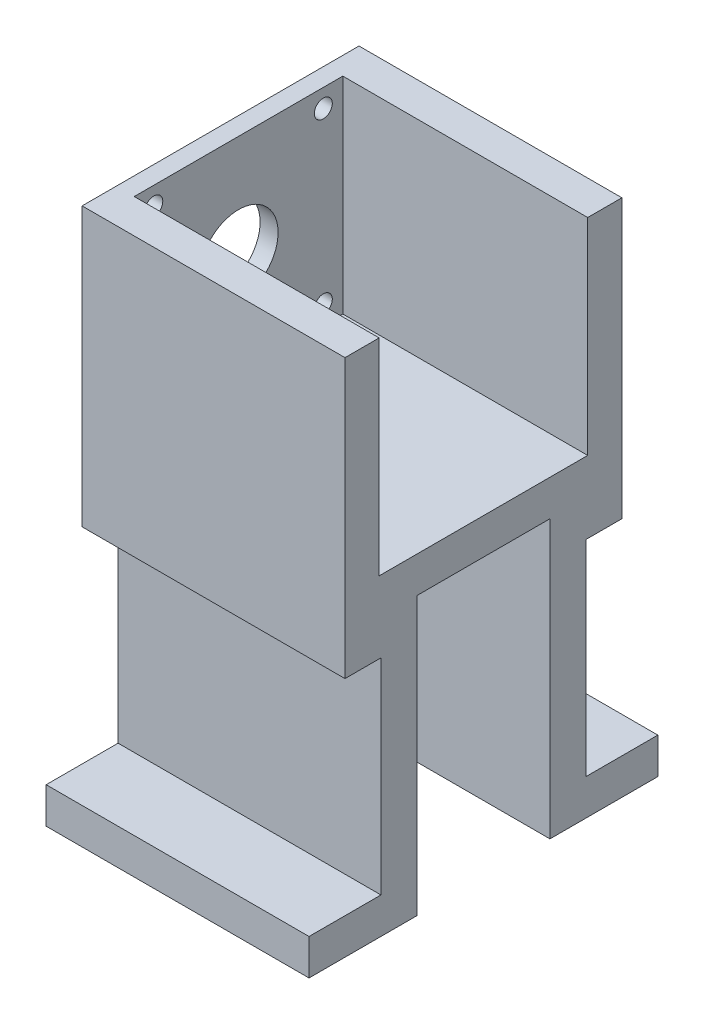
SolidWorks part; units mm, degrees
ref_plane "Front Plane" through (0, 0, 0) normal (0, 0, 1) x (1, 0, 0)
ref_plane "Top Plane" through (0, 0, 0) normal (0, 1, 0) x (1, 0, 0)
ref_plane "Right Plane" through (0, 0, 0) normal (1, 0, 0) x (0, 0, -1)
sketch "Sketch1" plane through (0, 0, 0) normal (0, 0, 1) x (1, 0, 0)
  line L0 (-34.05, 0) -> (34.05, 0)
  line L1 (-34.05, -10) -> (29.05, -10)
  line L2 (34.05, -10) -> (34.05, 0)
  line L3 (29.05, -10) -> (34.05, -10)
  line L4 (-39.05, 57.3) -> (-39.05, -10)
  line L7 (-34.05, -10) -> (-39.05, -10)
  line L8 (-39.05, 57.3) -> (-34.05, 57.3)
  line L9 (-34.05, 57.3) -> (-34.05, 0)
  dimension "D2" = 5
  dimension "D4" = 57.3
  dimension "D6" = 10
  dimension "D11" = 68.1
extrude "Boss-Extrude1" add sketch "Sketch1" along normal blind 57
sketch "Sketch4" plane through (-39.05, 0, 0) normal (-1, 0, 0) x (0, 0, 1)
  line L0 (28.5, 57.3) -> (28.5, 28.65) construction
  line L1 (57, 57.3) -> (0, 57.3) construction
  line L2 (4.93, 52.22) -> (28.5, 52.22) construction
  line L3 (52.07, 52.22) -> (28.5, 52.22) construction
  line L4 (28.5, 28.65) -> (57, 28.65) construction
  line L5 (57, 57.3) -> (57, -10) construction
  line L6 (52.07, 52.22) -> (52.07, 28.65) construction
  line L7 (52.07, 5.08) -> (52.07, 28.65) construction
  circle A0 centre (28.5, 28.65) radius 11
  circle A1 centre (52.07, 52.22) radius 2.5
  circle A2 centre (4.93, 52.22) radius 2.5
  circle A3 centre (52.07, 5.08) radius 2.5
  circle A4 centre (4.93, 5.08) radius 2.5
  dimension "D2" = 22
  dimension "D5" = 5
  dimension "D1" = 28.65
  dimension "D3" = 23.57
  dimension "D4" = 23.57
  dimension "D6" = 23.57
  dimension "D7" = 23.57
  dimension "D8" = 47.14
  dimension "D9" = 47.14
extrude "Cut-Extrude3" cut sketch "Sketch4" against normal blind 43
sketch "Sketch5" plane through (0, -10, 0) normal (0, -1, 0) x (1, 0, 0)
  line L0 (34.05, 57) -> (34.05, 0) construction
  line L1 (-39.05, 0) -> (34.05, 0)
  line L2 (-39.05, 0) -> (-39.05, 10)
  line L3 (-39.05, 10) -> (34.05, 10)
  line L4 (34.05, 0) -> (34.05, 10)
  line L5 (-39.05, 57) -> (-39.05, 0) construction
  line L6 (34.05, 57) -> (-39.05, 57)
  line L7 (34.05, 57) -> (34.05, 47)
  line L8 (34.05, 47) -> (-39.05, 47)
  line L9 (-39.05, 57) -> (-39.05, 47)
  dimension "D1" = 10
extrude "Boss-Extrude2" add sketch "Sketch5" along normal blind 77.1
sketch "Sketch6" plane through (0, 0, 0) normal (0, 0, -1) x (-1, 0, 0)
  line L0 (39.05, 57.3) -> (39.05, -87.1) construction
  line L1 (-34.05, -87.1) -> (39.05, -87.1)
  line L2 (-34.05, -87.1) -> (-34.05, -77.1)
  line L3 (-34.05, -77.1) -> (39.05, -77.1)
  line L4 (39.05, -87.1) -> (39.05, -77.1)
  dimension "D1" = 10
extrude "Boss-Extrude3" add sketch "Sketch6" along normal blind 20
ref_plane "Plane1" through (0, 0, 28.5) normal (0, 0, 1) x (1, 0, 0)
sketch "Sketch8" plane through (0, 0, 0) normal (0, 0, -1) x (-1, 0, 0)
  line L0 (-34.05, -77.1) -> (-34.05, 0) construction
  line L1 (39.05, 57.3) -> (-34.05, 57.3)
  line L2 (39.05, 57.3) -> (39.05, -20)
  line L3 (39.05, -20) -> (-34.05, -20)
  line L4 (-34.05, 57.3) -> (-34.05, -20)
  line L5 (-34.05, 0) -> (34.05, 0) construction
  dimension "D1" = 20
extrude "Boss-Extrude4" add sketch "Sketch8" along normal blind 10
mirror "Mirror2" about plane through (0, 0, 28.5) normal (0, 0, 1) of "Boss-Extrude4"
mirror "Mirror3" about plane through (0, 0, 28.5) normal (0, 0, 1) of "Boss-Extrude3"
sketch "Sketch9" plane through (0, 0, 57) normal (0, 0, -1) x (-1, 0, 0)
  line L4 (-34.05, 57.3) -> (-34.05, 0)
  line L5 (-34.05, 0) -> (34.05, 0)
  line L6 (34.05, 0) -> (34.05, 57.3)
  line L7 (34.05, 57.3) -> (-34.05, 57.3)
  line L8 (-34.05, 57.3) -> (-34.05, 0)
  line L9 (-34.05, 0) -> (34.05, 0)
  line L10 (34.05, 0) -> (34.05, 57.3)
  line L11 (34.05, 57.3) -> (-34.05, 57.3)
  dimension "D1" = 0
extrude "Cut-Extrude4" cut sketch "Sketch9" against normal blind 0.5
mirror "Mirror4" about plane through (0, 0, 28.5) normal (0, 0, 1) of "Cut-Extrude4"
